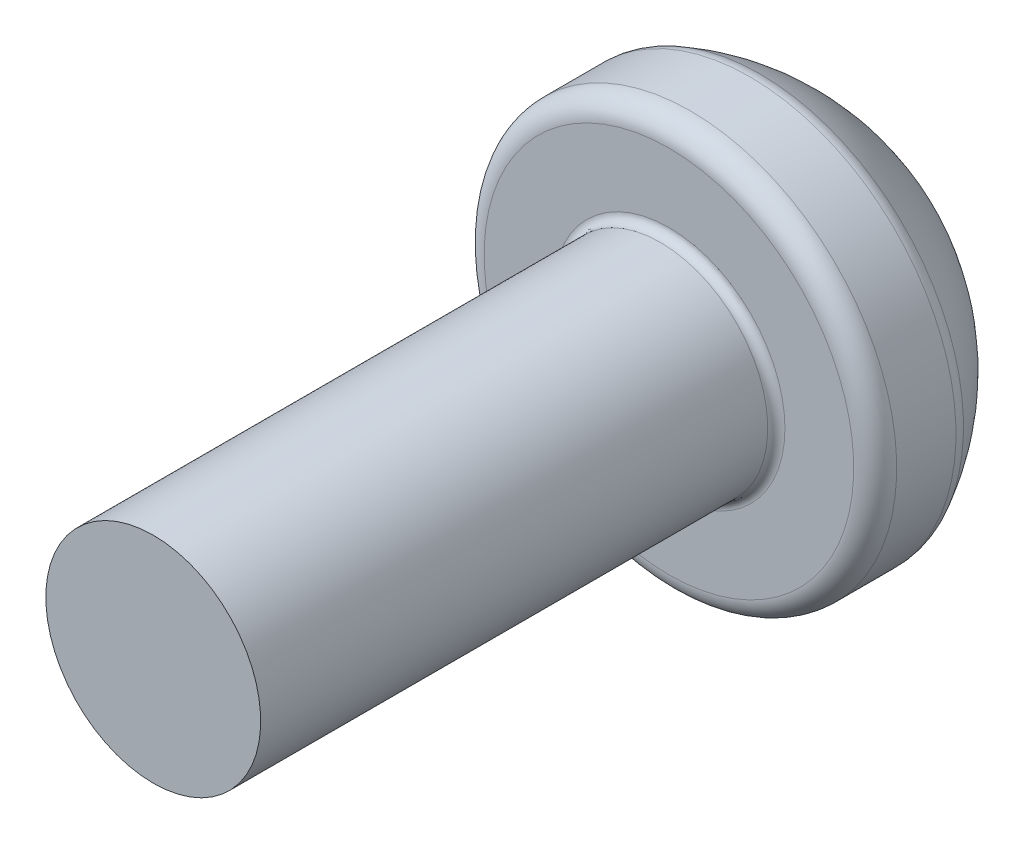
SolidWorks part; units mm, degrees
ref_plane "Plan1" through (0, 0, 0) normal (0, 0, 1) x (1, 0, 0)
ref_plane "Plan2" through (0, 0, 0) normal (0, 1, 0) x (1, 0, 0)
ref_plane "Plan3" through (0, 0, 0) normal (1, 0, 0) x (0, 0, -1)
sketch "Sketch1" plane through (0, 0, 0) normal (1, 0, 0) x (0, 0, -1)
  line L0 (2, 0) -> (-6, 0) construction
  line L1 (-6, 0) -> (-6, 1.25)
  line L2 (-6, 1.25) -> (0, 1.25)
  line L3 (0, 1.25) -> (0, 2.4)
  line L4 (0, 2.4) -> (1, 2.4)
  line L5 (2, 0) -> (2, 1.54)
  line L6 (2, 0) -> (-6, 0)
  line L7 (0, 0) -> (-0.5, 0) construction
  line L8 (0, 0) -> (0, 1.825) construction
  line L9 (0, 0) -> (0, 2.55) construction
  arc A0 (1, 2.4) -> (2, 1.54) centre (-0.1942, 0) cw
  dimension "D1" = 3.08
  dimension "D" = 2.5
  dimension "L" = 6
  dimension "D2" = 1
  dimension "K" = 2
  dimension "DK" = 4.8
  dimension "P" = 0.5
  dimension "DW" = 5.1
revolve "Base-Revolve" add sketch "Sketch1"
cosmetic thread "Cosmetic_Thread1"
fillet "Fillet1" radius 0.1 1 edges at (0, 1.25, 0)
fillet "Fillet2" radius 0.25 2 edges at (0, 2.4, -1) (0, 2.4, 0)
hole_wizard "Hole1" positions "Sketch3" profile "Sketch2" legacy
sketch "Sketch3" plane through (0, 0, -2) normal (0, 0, -1) x (-1, 0, 0)
  circle A0 centre (0, 0) radius 1.54 construction
  point P0 (0, 0)
sketch "Sketch2" plane through (0, 0, -2) normal (1, 0, 0) x (0, 1, 0)
  line L0 (0, 0) -> (0, 1.3731)
  line L1 (0, 1.3731) -> (1.025, 1)
  line L2 (1.025, 1) -> (1.025, 0)
  line L4 (1.025, 0) -> (0, 0)
  line L6 (0, 1.3731) -> (-1.025, 1) construction
  line L7 (0, -4.2442) -> (0, 117.3081) construction
  dimension "Diameter" = 2.05
  dimension "Depth" = 1
  dimension "Drill Angle" = 140
sketch "Sketch4" plane through (0, 0, -2) normal (0, 0, -1) x (-1, 0, 0)
  line L0 (0, 1.4) -> (0, -1.4) construction
  line L1 (0, 0) -> (0.8075, -1.3986) construction
  line L2 (0, 0) -> (-0.8075, -1.3986) construction
  line L3 (0, 0) -> (-1.615, 0) construction
  line L4 (0, 0) -> (-0.8075, 1.3986) construction
  line L5 (0, 0) -> (0.8075, 1.3986) construction
  line L6 (0, 0) -> (1.615, 0) construction
  arc A0 (1.0888, -0.88) -> (1.3065, -0.5029) centre (0, 0) ccw
  arc A1 (1.0888, -0.88) -> (0.2177, -1.383) centre (0.8075, -1.3986) ccw
  circle A2 centre (0, 0) radius 1.025 construction
  arc A3 (-0.2177, -1.383) -> (-1.0888, -0.88) centre (-0.8075, -1.3986) ccw
  arc A4 (-1.3065, -0.5029) -> (-1.3065, 0.5029) centre (-1.615, 0) ccw
  arc A5 (-1.0888, 0.88) -> (-0.2177, 1.383) centre (-0.8075, 1.3986) ccw
  arc A6 (0.2177, 1.383) -> (1.0888, 0.88) centre (0.8075, 1.3986) ccw
  arc A7 (1.3065, 0.5029) -> (1.3065, -0.5029) centre (1.615, 0) ccw
  arc A8 (1.3065, 0.5029) -> (1.0888, 0.88) centre (0, 0) ccw
  arc A9 (0.2177, 1.383) -> (-0.2177, 1.383) centre (0, 0) ccw
  arc A10 (-1.0888, 0.88) -> (-1.3065, 0.5029) centre (0, 0) ccw
  arc A11 (-1.3065, -0.5029) -> (-1.0888, -0.88) centre (0, 0) ccw
  arc A12 (-0.2177, -1.383) -> (0.2177, -1.383) centre (0, 0) ccw
  dimension "AE" = 2.8
  dimension "EE" = 0.59
  dimension "D2" = 30
  dimension "D4" = 30
  dimension "D5" = 30
  dimension "D6" = 30
extrude "Cut-Extrude1" cut sketch "Sketch4" against normal blind 1
equation "\"D2@Sketch1\" = \"Depth@Sketch2\""
equation "\"D1@Sketch1\" = 1.1*\"AE@Sketch4\""
equation "\"D1@Cosmetic_Thread1\" = \"D@Sketch1\"-(1.0825*\"P@Sketch1\")"
equation "\"D1@Fillet2\" = (\"DK@Sketch1\"-\"DW@Sketch1\")/2"
equation "\"T@Cut-Extrude1\" = \"Depth@Sketch2\""
